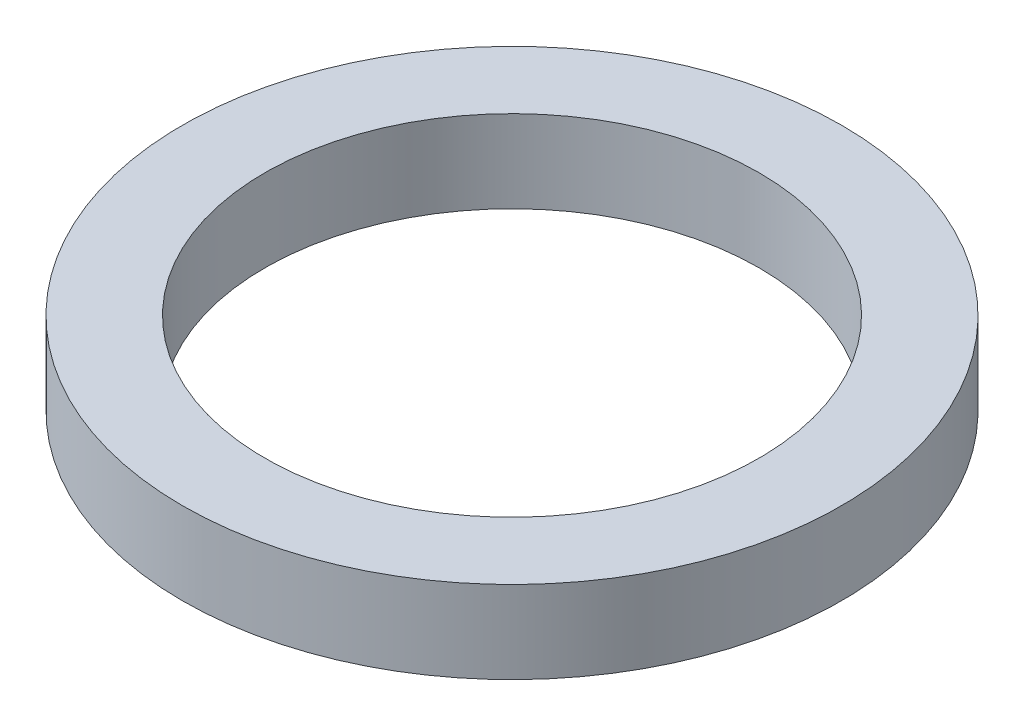
SolidWorks part; units mm, degrees
ref_plane "前视基准面" through (0, 0, 0) normal (0, 0, 1) x (1, 0, 0)
ref_plane "上视基准面" through (0, 0, 0) normal (0, 1, 0) x (1, 0, 0)
ref_plane "右视基准面" through (0, 0, 0) normal (1, 0, 0) x (0, 0, -1)
other "Configuration Table"
sketch "草图1" plane through (0, 0, 0) normal (0, 0, 1) x (1, 0, 0)
  line L0 (0, -100) -> (0, 100) construction
  line L2 (300, -50) -> (400, -50)
  line L3 (300, -50) -> (300, 50)
  line L4 (300, 50) -> (400, 50)
  line L5 (400, -50) -> (400, 50)
revolve "旋转1" add sketch "草图1" angle 360 about L0
